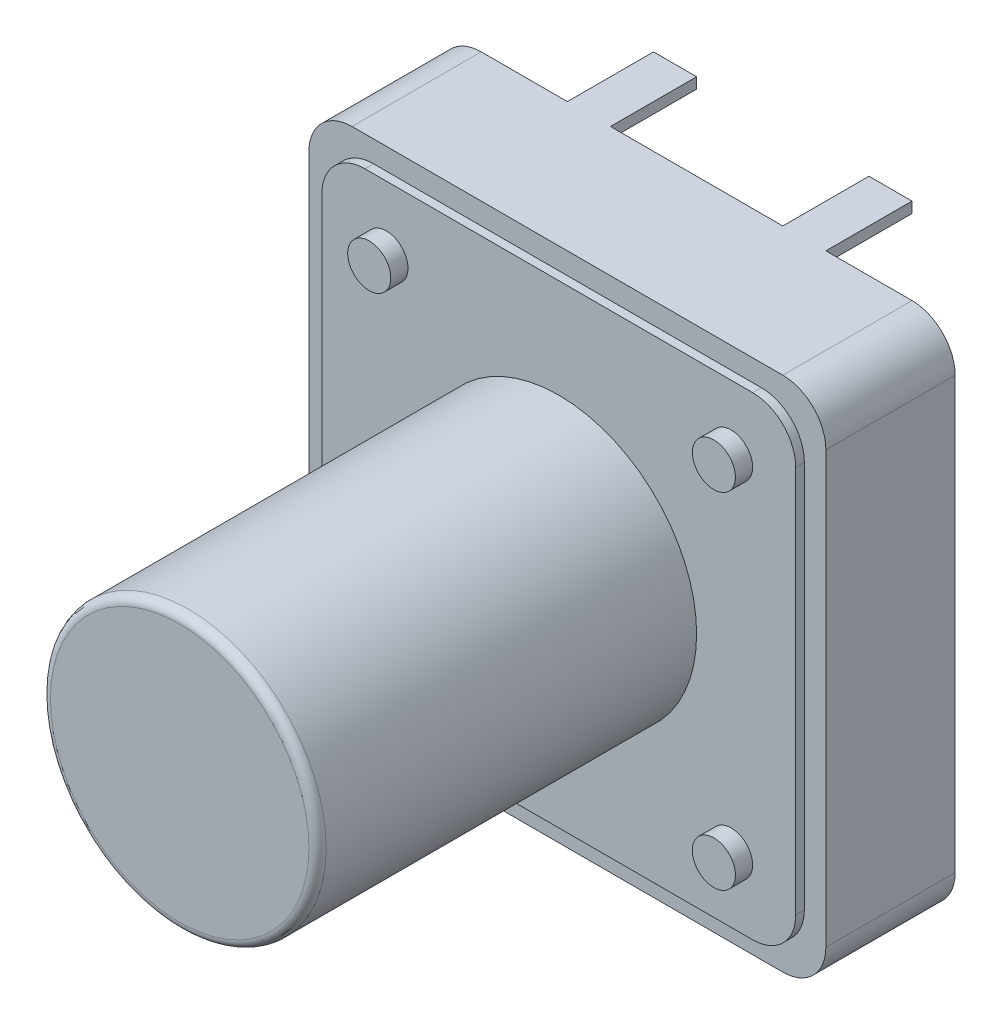
SolidWorks part; units mm, degrees
ref_plane "前视基准面" through (0, 0, 0) normal (0, 0, 1) x (1, 0, 0)
ref_plane "上视基准面" through (0, 0, 0) normal (0, 1, 0) x (1, 0, 0)
ref_plane "右视基准面" through (0, 0, 0) normal (1, 0, 0) x (0, 0, -1)
sketch "草图1" plane through (0, 0, 0) normal (0, 0, 1) x (1, 0, 0)
  line L1 (1, 0) -> (11, 0)
  line L2 (0, -1) -> (0, -11)
  line L3 (1, -12) -> (11, -12)
  line L4 (12, -1) -> (12, -11)
  arc A0 (1, -12) -> (0, -11) centre (1, -11) cw
  arc A1 (11, -12) -> (12, -11) centre (11, -11) ccw
  arc A2 (12, -1) -> (11, 0) centre (11, -1) ccw
  arc A3 (0, -1) -> (1, 0) centre (1, -1) cw
  point P13 (0, 0)
  dimension "D3" = 1
  dimension "D1" = 12
  dimension "D2" = 12
extrude "凸台-拉伸1" add sketch "草图1" along normal blind 3
sketch "草图2" plane through (0, 0, 3) normal (0, 0, 1) x (1, 0, 0)
  line L0 (6, 0) -> (6, -12) construction
  line L1 (11, 0) -> (1, 0) construction
  line L2 (1, -12) -> (11, -12) construction
  line L3 (0, -6) -> (12, -6) construction
  line L4 (0, -1) -> (0, -11) construction
  line L5 (12, -11) -> (12, -1) construction
  circle A0 centre (6, -6) radius 3.2
  dimension "D1" = 6.4
extrude "凸台-拉伸2" add sketch "草图2" along normal blind 9
fillet "圆角1" radius 0.2 1 edges at (9.2, -6, 12)
sketch "草图3" plane through (0, 0, 3) normal (0, 0, 1) x (1, 0, 0)
  line L0 (1.5, -0.5) -> (10.5, -0.5)
  line L1 (11.5, -1.5) -> (11.5, -10.5)
  line L2 (10.5, -11.5) -> (1.5, -11.5)
  line L3 (0.5, -10.5) -> (0.5, -1.5)
  circle A0 centre (6, -6) radius 5.5 construction
  arc A1 (0.5, -10.5) -> (1.5, -11.5) centre (1.5, -10.5) ccw
  arc A2 (10.5, -11.5) -> (11.5, -10.5) centre (10.5, -10.5) ccw
  arc A3 (11.5, -1.5) -> (10.5, -0.5) centre (10.5, -1.5) ccw
  arc A4 (1.5, -0.5) -> (0.5, -1.5) centre (1.5, -1.5) ccw
  dimension "D1" = 11
  dimension "D2" = 1
extrude "凸台-拉伸3" add sketch "草图3" along normal blind 0.2
sketch "草图4" plane through (0, 0, 3.2) normal (0, 0, 1) x (1, 0, 0)
  line L0 (11, 0) -> (1, 0) construction
  line L1 (0, -1) -> (0, -11) construction
  line L2 (6, -0.5) -> (6, -11.5) construction
  line L3 (10.5, -0.5) -> (1.5, -0.5) construction
  line L4 (1.5, -11.5) -> (10.5, -11.5) construction
  line L5 (0.5, -6) -> (11.5, -6) construction
  line L6 (0.5, -1.5) -> (0.5, -10.5) construction
  line L7 (11.5, -10.5) -> (11.5, -1.5) construction
  circle A0 centre (2, -2) radius 0.5
  circle A1 centre (10, -2) radius 0.5
  circle A2 centre (10, -10) radius 0.5
  circle A3 centre (2, -10) radius 0.5
  dimension "D1" = 1
  dimension "D2" = 2
  dimension "D3" = 2
extrude "凸台-拉伸4" add sketch "草图4" along normal blind 0.4
sketch "草图5" plane through (0, 0, 0) normal (0, 0, -1) x (-1, 0, 0)
  line L0 (-6, -12) -> (-6, 0) construction
  line L1 (-1, -12) -> (-11, -12) construction
  line L2 (-11, 0) -> (-1, 0) construction
  line L3 (-3.5, -12.7527) -> (-3.5, -10.7949) construction
  line L4 (-3, -12) -> (-3, -11.75)
  line L5 (-4, -12) -> (-4, -11.75)
  line L6 (-3, -12) -> (-4, -12)
  line L7 (-3, -11.75) -> (-4, -11.75)
  line L8 (-8, -12) -> (-8, -11.75)
  line L9 (-9, -11.75) -> (-8, -11.75)
  line L10 (-9, -12) -> (-8, -12)
  line L11 (-9, -12) -> (-9, -11.75)
  line L12 (0, -6) -> (-12, -6) construction
  line L13 (0, -1) -> (0, -11) construction
  line L14 (-12, -11) -> (-12, -1) construction
  line L15 (-9, 0) -> (-8, 0)
  line L16 (-9, 0) -> (-9, -0.25)
  line L17 (-9, -0.25) -> (-8, -0.25)
  line L18 (-8, 0) -> (-8, -0.25)
  line L19 (-4, 0) -> (-4, -0.25)
  line L20 (-3, 0) -> (-3, -0.25)
  line L21 (-3, 0) -> (-4, 0)
  line L22 (-3, -0.25) -> (-4, -0.25)
  dimension "D1" = 2.5
  dimension "D2" = 0.25
  dimension "D3" = 1
extrude "凸台-拉伸5" add sketch "草图5" along normal blind 2
